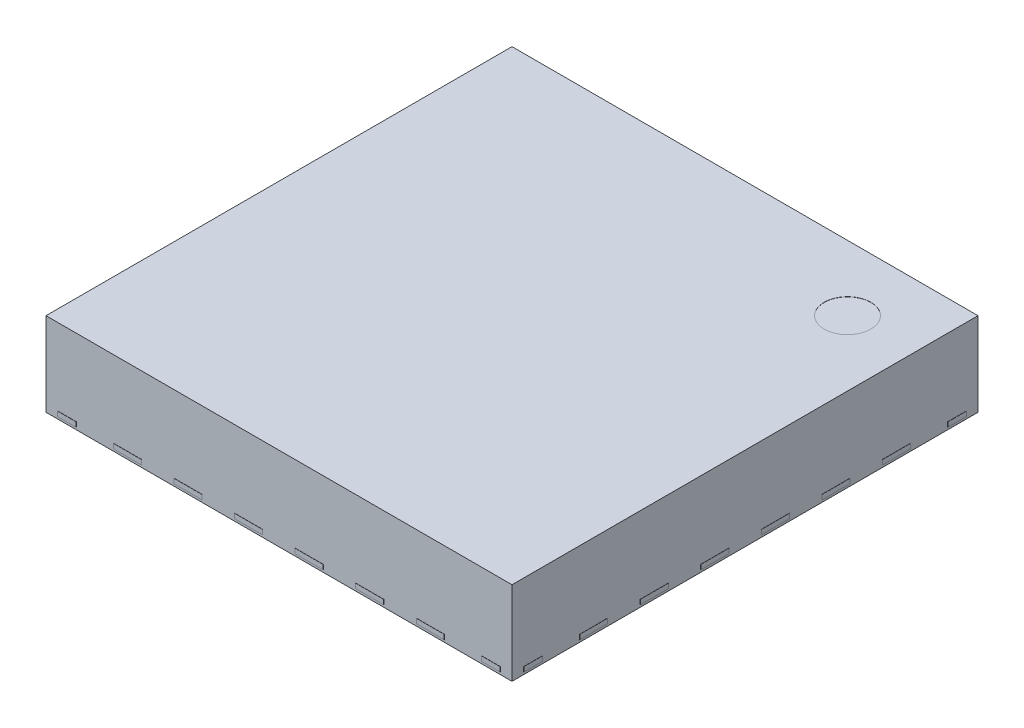
SolidWorks part; units mm, degrees
ref_plane "Front" through (0, 0, 0) normal (0, 0, 1) x (1, 0, 0)
ref_plane "Top" through (0, 0, 0) normal (0, 1, 0) x (1, 0, 0)
ref_plane "Right" through (0, 0, 0) normal (1, 0, 0) x (0, 0, -1)
sketch "Sketch1" plane through (0, 0, 0) normal (0, 1, 0) x (1, 0, 0)
  line L0 (-3.6959, 0) -> (3.4221, 0) construction
  line L1 (-2.5, 2.5) -> (2.5, 2.5)
  line L2 (-2.5, 2.5) -> (-2.5, -2.5)
  line L3 (-2.5, -2.5) -> (2.5, -2.5)
  line L4 (2.5, 2.5) -> (2.5, -2.5)
  line L5 (0, -3.4711) -> (0, 4.6299) construction
  point P9 (0, 2.5)
  point P10 (-2.5, 0)
  dimension "D1" = 5
extrude "Extrude1" add sketch "Sketch1" along normal blind 0.898 from offset 0.002
sketch "Sketch2" plane through (0, 0, 0) normal (0, 1, 0) x (1, 0, 0)
  line L0 (0, 5.0686) -> (0, -5.0012) construction
  line L1 (-5.1513, 0) -> (5.0839, 0) construction
  line L2 (2.5, -2.5) -> (2.5, 2.5) construction
  line L3 (-2.5, -2.5) -> (2.5, -2.5) construction
  line L4 (2.5, 2.5) -> (-2.5, 2.5) construction
  line L5 (0.175, 2.4425) -> (0.475, 2.4425)
  line L6 (0.175, 2.4425) -> (0.175, 2.255)
  line L8 (0.475, 2.4425) -> (0.475, 2.255)
  arc A0 (0.175, 2.255) -> (0.475, 2.255) centre (0.325, 2.255) ccw
  point P6 (2.5, 0)
  point P9 (0, -2.5)
  point P16 (0.325, 2.4425)
  dimension "D1" = 0.1875
  dimension "D2" = 0.3
  dimension "D3" = 0.65
  dimension "D4" = 0.0575
extrude "Extrude2" add sketch "Sketch2" along normal blind 0.002
sketch "Sketch3" plane through (0, 0, 0) normal (0, 1, 0) x (1, 0, 0)
  line L0 (0, 3.1871) -> (0, -3.6549) construction
  line L1 (-4.3634, 0) -> (3.6711, 0) construction
  line L2 (-2.5, 2.5) -> (-2.5, -2.5) construction
  line L10 (-2.4425, 0.175) -> (-2.1425, 0.175)
  line L11 (-2.4425, 0.175) -> (-2.4425, 0.475)
  line L12 (-2.4425, 0.475) -> (-2.1425, 0.475)
  line L14 (-2.5, -2.5) -> (2.5, -2.5) construction
  line L15 (2.5, -2.5) -> (2.5, 2.5) construction
  arc A0 (-2.1425, 0.475) -> (-2.1425, 0.175) centre (-2.1425, 0.325) cw
  point P6 (0, -2.5)
  point P9 (2.5, 0)
  point P23 (-2.4425, 0.325)
  dimension "D1" = 0.0575
  dimension "D2" = 0.3
  dimension "D3" = 0.3
  dimension "D4" = 0.65
extrude "Extrude3" add sketch "Sketch3" along normal blind 0.002
sketch "Sketch6" plane through (0, 0.002, 0) normal (0, -1, 0) x (-1, 0, 0)
  line L1 (-0.475, 2.502) -> (-0.175, 2.502)
  line L2 (-0.475, 2.502) -> (-0.475, 2.5)
  line L3 (-0.475, 2.5) -> (-0.175, 2.5)
  line L4 (-0.175, 2.502) -> (-0.175, 2.5)
  line L5 (-2.5, 2.5) -> (2.5, 2.5) construction
  line L7 (-0.475, 2.255) -> (-0.475, 2.4425) construction
  line L8 (-0.175, 2.4425) -> (-0.175, 2.255) construction
  dimension "D1" = 0.002
extrude "Extrude5" add sketch "Sketch6" against normal blind 0.05 from offset 0.025 offset against normal yes
sketch "Sketch7" plane through (0, 0.002, 0) normal (0, 1, 0) x (1, 0, 0)
  line L1 (-2.502, 0.475) -> (-2.5, 0.475)
  line L2 (-2.502, 0.475) -> (-2.502, 0.175)
  line L3 (-2.502, 0.175) -> (-2.5, 0.175)
  line L4 (-2.5, 0.475) -> (-2.5, 0.175)
  line L5 (-2.1425, 0.475) -> (-2.4425, 0.475) construction
  line L6 (-2.4425, 0.175) -> (-2.1425, 0.175) construction
  line L7 (-2.5, 2.5) -> (-2.5, -2.5) construction
  dimension "D1" = 0.002
extrude "Extrude6" add sketch "Sketch7" along normal blind 0.05 from offset 0.025
pattern_linear "LPattern1" count 4 spacing 0.65 along (1, 0, 0) count 5 spacing 0.65 along (-1, 0, 0) of "Extrude2", "Extrude5"
pattern_linear "LPattern2" count 4 spacing 0.65 along (0, 0, -1) count 5 spacing 0.65 along (0, 0, 1) of "Extrude3", "Extrude6"
mirror "Mirror1" about plane through (0, 0, 0) normal (0, 0, 1) of "Extrude2", "LPattern1", "Extrude5"
mirror "Mirror2" about plane through (0, 0, 0) normal (1, 0, 0) of "Extrude6", "Extrude3", "LPattern2"
sketch "Sketch4" plane through (0, 0.002, 0) normal (0, -1, 0) x (1, 0, 0)
  line L0 (0, -4.6014) -> (0, 4.7728) construction
  line L1 (-1.7232, 1.9) -> (1.723, 1.9)
  line L2 (-1.9, 1.7232) -> (-1.9, -1.7232)
  line L3 (-1.7232, -1.9) -> (1.7232, -1.9)
  line L4 (1.723, 1.9) -> (1.9, 1.723)
  line L5 (-4.7514, 0) -> (4.9371, 0) construction
  line L6 (1.9, 1.723) -> (1.9, -1.7232)
  line L7 (2.9308, -2.9308) -> (-2.9536, 2.9536) construction
  line L8 (-2.8061, -2.8061) -> (2.6783, 2.6783) construction
  line L9 (-2, -2.1768) -> (-1.7232, -1.9)
  line L10 (2.1768, -2) -> (1.9, -1.7232)
  line L11 (-2.1768, -2) -> (-1.9, -1.7232)
  line L12 (2, -2.1768) -> (1.7232, -1.9)
  line L13 (-2.1768, 2) -> (-2, 2.1768)
  line L14 (-2, -2.1768) -> (-2.1768, -2)
  line L15 (2, -2.1768) -> (2.1768, -2)
  line L16 (3.0192, -2.8424) -> (-2.8652, 3.042) construction
  line L17 (2.8424, -3.0192) -> (-3.042, 2.8652) construction
  line L19 (-1.7232, 1.9) -> (-2, 2.1768)
  line L20 (-2.7177, -2.8945) -> (2.7667, 2.5899) construction
  line L21 (-2.8945, -2.7177) -> (2.5899, 2.7667) construction
  line L22 (-1.9, 1.7232) -> (-2.1768, 2)
  dimension "D2" = 0.177
  dimension "D1" = 3.8
  dimension "D3" = 0.177
  dimension "D4" = 0.2503
  dimension "D5" = 3.8
  dimension "D8" = 2
  dimension "D9" = 2
  dimension "D10" = 45
  dimension "D11" = 45
  dimension "D6" = 0.125
  dimension "D7" = 0.125
extrude "Extrude4" add sketch "Sketch4" along normal blind 0.002
sketch "Sketch5" plane through (0, 0.9, 0) normal (0, 1, 0) x (1, 0, 0)
  circle A0 centre (1.8, 1.8) radius 0.25
  dimension "D1" = 0.5
  dimension "D2" = 1.8
  dimension "D3" = 1.8
extrude "Cut-Extrude1" cut sketch "Sketch5" against normal blind 0.002
sketch "Sketch11" plane through (0, 0, -2.502) normal (0, 0, -1) x (-1, 0, 0)
  line L0 (2.125, 0.027) -> (2.425, 0.027) construction
  line L1 (2.425, 0.077) -> (2.375, 0.077)
  line L2 (2.425, 0.077) -> (2.425, 0.027)
  line L3 (2.425, 0.027) -> (2.375, 0.027)
  line L4 (2.375, 0.077) -> (2.375, 0.027)
  line L5 (2.425, 0.027) -> (2.125, 0.027) construction
  line L6 (2.125, 0.077) -> (2.175, 0.077)
  line L7 (2.125, 0.077) -> (2.125, 0.027)
  line L8 (2.125, 0.027) -> (2.175, 0.027)
  line L9 (2.175, 0.077) -> (2.175, 0.027)
  line L10 (0, -0.6542) -> (0, 1.9103) construction
  line L11 (-2.175, 0.077) -> (-2.175, 0.027)
  line L12 (-2.125, 0.027) -> (-2.175, 0.027)
  line L13 (-2.125, 0.077) -> (-2.125, 0.027)
  line L14 (-2.125, 0.077) -> (-2.175, 0.077)
  line L15 (-2.375, 0.077) -> (-2.375, 0.027)
  line L16 (-2.425, 0.027) -> (-2.375, 0.027)
  line L17 (-2.425, 0.077) -> (-2.425, 0.027)
  line L18 (-2.425, 0.077) -> (-2.375, 0.077)
  line M1 (2.125, 0.027) -> (2.425, 0.027)
  line M2 (2.425, 0.027) -> (2.425, 0.077)
  line M3 (2.425, 0.077) -> (2.125, 0.077)
  line M4 (2.125, 0.077) -> (2.125, 0.027)
  dimension "D1" = 0.05
  dimension "D2" = 0.05
extrude "Cut-Extrude5" cut sketch "Sketch11" against normal blind 0.002 contours L18 L17 L16 L15 | L13 L14 L11 L12 | L9 M3 M4 M1 | L4 M3 M1 M2
mirror "Mirror3" about plane through (0, 0, 0) normal (0, 0, 1) of "Cut-Extrude5"
sketch "Sketch13" plane through (2.502, 0, 0) normal (1, 0, 0) x (0, 0, -1)
  line L0 (2.125, 0.027) -> (2.425, 0.027) construction
  line L1 (2.425, 0.077) -> (2.375, 0.077)
  line L2 (2.425, 0.077) -> (2.425, 0.027)
  line L3 (2.425, 0.027) -> (2.375, 0.027)
  line L4 (2.375, 0.077) -> (2.375, 0.027)
  line L5 (0, -0.492) -> (0, 1.7935) construction
  line L6 (2.125, 0.077) -> (2.175, 0.077)
  line L7 (2.125, 0.077) -> (2.125, 0.027)
  line L8 (2.125, 0.027) -> (2.175, 0.027)
  line L9 (2.175, 0.077) -> (2.175, 0.027)
  line L10 (-2.175, 0.077) -> (-2.175, 0.027)
  line L11 (-2.125, 0.027) -> (-2.175, 0.027)
  line L12 (-2.125, 0.077) -> (-2.125, 0.027)
  line L13 (-2.125, 0.077) -> (-2.175, 0.077)
  line L14 (-2.375, 0.077) -> (-2.375, 0.027)
  line L15 (-2.425, 0.027) -> (-2.375, 0.027)
  line L16 (-2.425, 0.077) -> (-2.425, 0.027)
  line L17 (-2.425, 0.077) -> (-2.375, 0.077)
  line M1 (2.125, 0.027) -> (2.425, 0.027)
  line M2 (2.425, 0.027) -> (2.425, 0.077)
  line M3 (2.425, 0.077) -> (2.125, 0.077)
  line M4 (2.125, 0.077) -> (2.125, 0.027)
  dimension "D1" = 0.05
  dimension "D2" = 0.05
extrude "Cut-Extrude6" cut sketch "Sketch13" against normal blind 0.002 contours L9 M3 M4 M1 | L4 M3 M1 M2 | L17 L16 L15 L14 | L12 L13 L10 L11
mirror "Mirror4" about plane through (0, 0, 0) normal (1, 0, 0) of "Cut-Extrude6"
